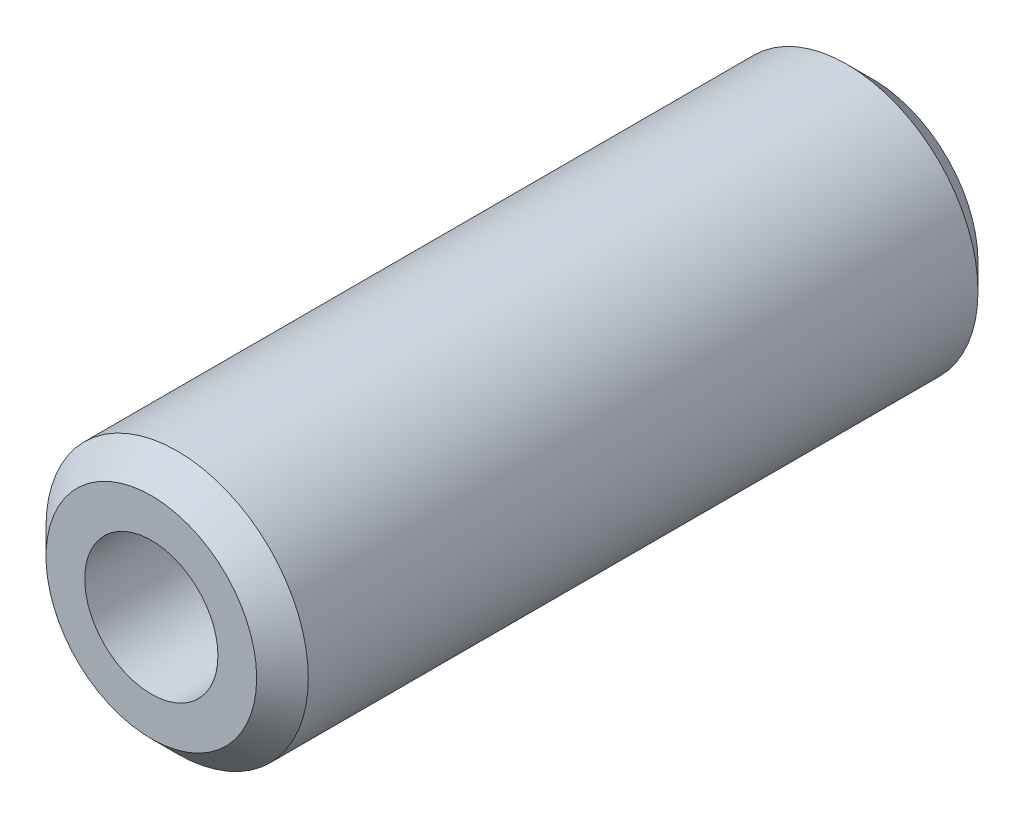
SolidWorks part; units mm, degrees
ref_plane "Front Plane" through (0, 0, 0) normal (0, 0, 1) x (1, 0, 0)
ref_plane "Top Plane" through (0, 0, 0) normal (0, 1, 0) x (1, 0, 0)
ref_plane "Right Plane" through (0, 0, 0) normal (1, 0, 0) x (0, 0, -1)
sketch "Sketch1" plane through (0, 0, 0) normal (0, 0, 1) x (1, 0, 0)
  circle A0 centre (0, 0) radius 12.7
  circle A2 centre (0, 0) radius 6.45
  dimension "D1" = 25.4
  dimension "D2" = 12.9
extrude "Boss-Extrude1" add sketch "Sketch1" along normal blind 69.85
chamfer "Chamfer1" distance 2.5 angle 45 2 edges at (12.7, 0, 0) (12.7, 0, 69.85)
